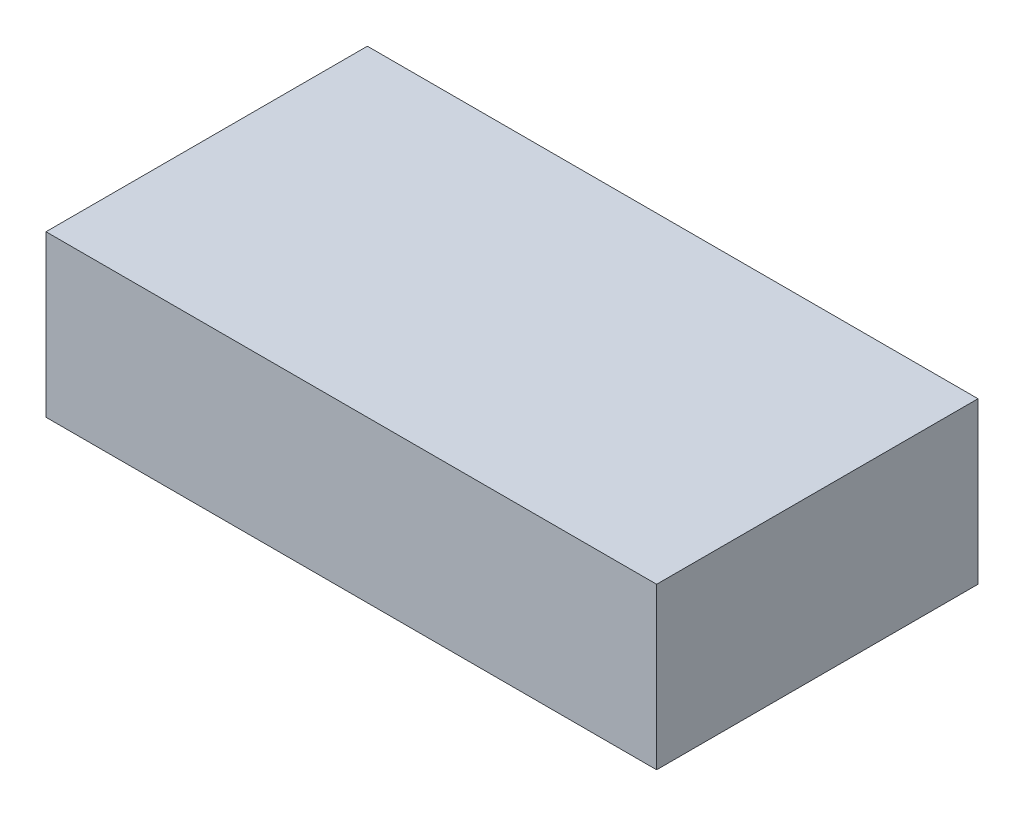
SolidWorks part; units mm, degrees
ref_plane "Front Plane" through (0, 0, 0) normal (0, 0, 1) x (1, 0, 0)
ref_plane "Top Plane" through (0, 0, 0) normal (0, 1, 0) x (1, 0, 0)
ref_plane "Right Plane" through (0, 0, 0) normal (1, 0, 0) x (0, 0, -1)
sketch "Sketch1" plane through (0, 0, 0) normal (0, 1, 0) x (1, 0, 0)
  line L1 (27.5142, 58.7513) -> (103.5142, 58.7513)
  line L2 (27.5142, 58.7513) -> (27.5142, 18.7513)
  line L3 (27.5142, 18.7513) -> (103.5142, 18.7513)
  line L4 (103.5142, 58.7513) -> (103.5142, 18.7513)
  dimension "D1" = 76
  dimension "D2" = 40
extrude "Boss-Extrude1" add sketch "Sketch1" along normal blind 20
